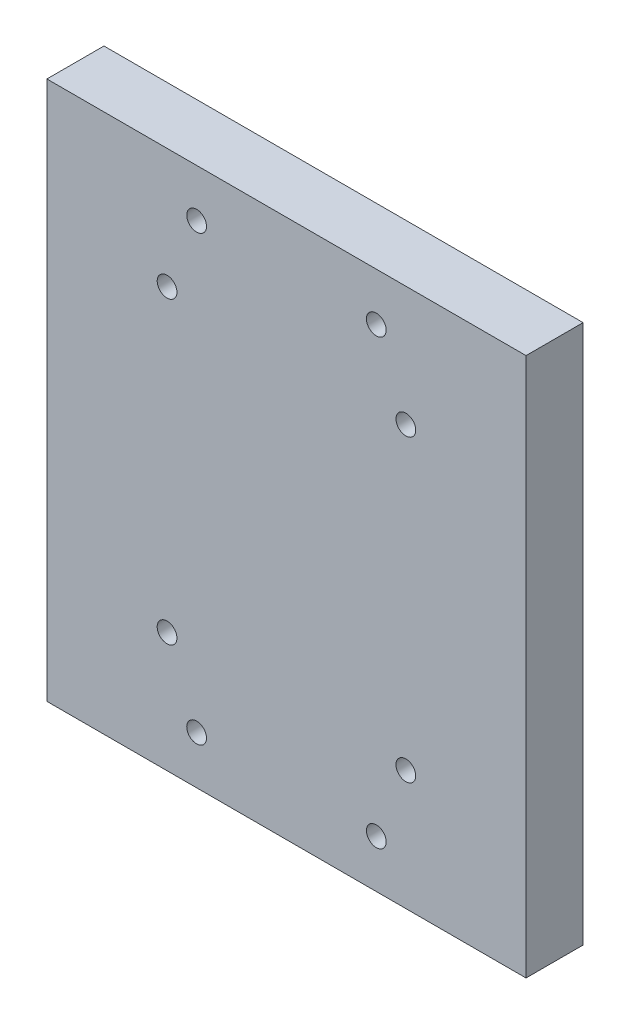
SolidWorks part; units mm, degrees
ref_plane "Front Plane" through (0, 0, 0) normal (0, 0, 1) x (1, 0, 0)
ref_plane "Top Plane" through (0, 0, 0) normal (0, 1, 0) x (1, 0, 0)
ref_plane "Right Plane" through (0, 0, 0) normal (1, 0, 0) x (0, 0, -1)
sketch "Sketch1" plane through (0, 0, 0) normal (0, 0, 1) x (1, 0, 0)
  line L1 (0, 0) -> (80, 0)
  line L2 (0, 0) -> (0, 90)
  line L3 (0, 90) -> (80, 90)
  line L4 (80, 0) -> (80, 90)
  circle A0 centre (55, 8) radius 1.65
  circle A1 centre (25, 8) radius 1.65
  circle A2 centre (55, 82) radius 1.65
  circle A3 centre (25, 82) radius 1.65
  dimension "D8" = 3.3
  dimension "D9" = 3.3
  dimension "D10" = 3.3
  dimension "D11" = 3.3
  dimension "D1" = 90
  dimension "D2" = 80
  dimension "D3" = 30
  dimension "D4" = 74
  dimension "D5" = 30
  dimension "D6" = 8
  dimension "D7" = 25
extrude "Boss-Extrude1" add sketch "Sketch1" along normal blind 9.53 contours A3 | A2 | A0 | A1 | L1 L4 L3 L2 A3 A2 A1 A0
sketch "Sketch4" plane through (0, 0, 9.53) normal (0, 0, 1) x (1, 0, 0)
  line L4 (0, 0) -> (80, 0)
  line L5 (80, 0) -> (80, 90)
  line L6 (80, 90) -> (0, 90)
  line L7 (0, 90) -> (0, 0)
  line L8 (0, 0) -> (80, 0)
  line L9 (80, 0) -> (80, 90)
  line L10 (80, 90) -> (0, 90)
  line L11 (0, 90) -> (0, 0)
  circle A0 centre (20.065, 70) radius 1.9329
  circle A1 centre (25, 82) radius 1.65
  circle A2 centre (25, 82) radius 1.65
  circle A3 centre (55, 82) radius 1.65
  circle A4 centre (55, 82) radius 1.65
  circle A5 centre (25, 8) radius 1.65
  circle A6 centre (25, 8) radius 1.65
  circle A7 centre (55, 8) radius 1.65
  circle A8 centre (55, 8) radius 1.65
  circle A17 centre (59.935, 70) radius 1.6481
  circle A18 centre (59.935, 20) radius 1.5221
  circle A19 centre (20.065, 20) radius 1.8109
  dimension "D10" = 20
  dimension "D11" = 20
  dimension "D12" = 20
  dimension "D13" = 20.065
  dimension "D6" = 20.065
  dimension "D7" = 20
  dimension "D8" = 20.065
  dimension "D9" = 20.065
  dimension "D1" = 0
  dimension "D2" = 0
  dimension "D3" = 0
  dimension "D4" = 0
  dimension "D5" = 0
hole_wizard "M4x0.7 Tapped Hole1" positions "3DSketch5" profile "Sketch6" tap size "M4x0.7" standard "Ansi Metric" end condition through all
sketch3d "3DSketch5"
  point P0 (20.065, 70, 9.53)
  point P3 (59.935, 70, 9.53)
  point P6 (59.935, 20, 9.53)
  point P9 (20.065, 20, 9.53)
sketch "Sketch6" plane through (20.065, 70, 9.53) normal (1, 0, 0) x (0, -1, 0)
  line L0 (0, 0) -> (0, 9.53)
  line L1 (0, 9.53) -> (1.65, 9.53)
  line L2 (1.65, 9.53) -> (1.65, 0)
  line L5 (1.65, 0) -> (0, 0)
  line L11 (0, -6.35) -> (0, 107.95) construction
  dimension "Thru Tap Drill Dia." = 3.3
  dimension "Thru Tap Drill Depth" = 9.53
cosmetic thread "Hole Thread9" parameters "D2"=4
cosmetic thread "Hole Thread10" parameters "D2"=4
cosmetic thread "Hole Thread11" parameters "D2"=4
cosmetic thread "Hole Thread12" parameters "D2"=4
sketch "Sketch7" plane through (0, 0, 0) normal (0, 0, -1) x (-1, 0, 0)
  line L4 (-80, 0) -> (0, 0)
  line L5 (-80, 90) -> (-80, 0)
  line L6 (0, 90) -> (-80, 90)
  line L7 (0, 0) -> (0, 90)
  line L8 (-80, 0) -> (0, 0)
  line L9 (-80, 90) -> (-80, 0)
  line L10 (0, 90) -> (-80, 90)
  line L11 (0, 0) -> (0, 90)
  circle A1 centre (-25, 82) radius 1.65
  circle A2 centre (-25, 82) radius 1.65
  circle A3 centre (-55, 82) radius 1.65
  circle A4 centre (-55, 82) radius 1.65
  circle A5 centre (-25, 8) radius 1.65
  circle A6 centre (-25, 8) radius 1.65
  circle A7 centre (-55, 8) radius 1.65
  circle A8 centre (-55, 8) radius 1.65
  dimension "D1" = 0
  dimension "D2" = 0
  dimension "D3" = 0
  dimension "D4" = 0
  dimension "D5" = 0
hole_wizard "M4x0.7 Tapped Hole2" positions "3DSketch6" profile "Sketch8" tap size "M4x0.7" standard "Ansi Metric" end condition through all
sketch3d "3DSketch6"
  point P0 (55, 8, 0)
  point P3 (25, 8, 0)
  point P6 (25, 82, 0)
  point P9 (55, 82, 0)
sketch "Sketch8" plane through (55, 8, 0) normal (1, 0, 0) x (0, 1, 0)
  line L0 (0, 0) -> (0, 9.53)
  line L1 (0, 9.53) -> (1.65, 9.53)
  line L2 (1.65, 9.53) -> (1.65, 0)
  line L5 (1.65, 0) -> (0, 0)
  line L11 (0, -6.35) -> (0, 107.95) construction
  dimension "Thru Tap Drill Dia." = 3.3
  dimension "Thru Tap Drill Depth" = 9.53
cosmetic thread "Hole Thread13" parameters "D2"=4
cosmetic thread "Hole Thread14" parameters "D2"=4
cosmetic thread "Hole Thread15" parameters "D2"=4
cosmetic thread "Hole Thread16" parameters "D2"=4
